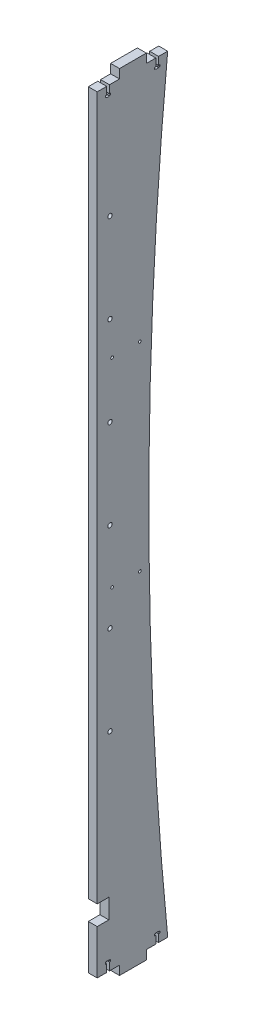
SolidWorks part; units mm, degrees
ref_plane "Płaszczyzna przednia" through (0, 0, 0) normal (0, 0, 1) x (1, 0, 0)
ref_plane "Płaszczyzna górna" through (0, 0, 0) normal (0, 1, 0) x (1, 0, 0)
ref_plane "Płaszczyzna prawa" through (0, 0, 0) normal (1, 0, 0) x (0, 0, -1)
ref_plane "Płaszczyzna2" through (248.5228, 0, 0) normal (-1, 0, 0) x (0, 0, 1)
sketch "Szkic11" plane through (248.5228, 0, 0) normal (-1, 0, 0) x (0, 0, 1)
  line L0 (-79.0014, 0) -> (0, 0)
  line L1 (0, 880) -> (-78.9552, 880)
  line L2 (-78.9552, 870) -> (-78.9552, 880)
  line L4 (-79.0014, 10) -> (-79.0014, 0)
  line L13 (0, 0) -> (0, 880)
  arc A2 (-79.0014, 10) -> (-78.9552, 870) centre (-4437.8003, 440.2341) ccw
extrude "Dodanie-wyciągnięcie1" add sketch "Szkic11" along normal blind 10
sketch "Szkic1" plane through (248.5228, 0, 0) normal (1, 0, 0) x (0, 0, -1)
  line L0 (85, 880) -> (85, 869.9)
  line L1 (85, 880) -> (55, 880)
  line L2 (85, 869.9) -> (55, 869.9)
  line L3 (55, 880) -> (55, 869.9)
  line L5 (25, 880) -> (25, 869.9)
  line L6 (25, 880) -> (0, 880)
  line L7 (25, 869.9) -> (0, 869.9)
  line L8 (0, 880) -> (0, 869.9)
  line L9 (0, 880) -> (78.9552, 880) construction
  dimension "D1" = 25
  dimension "D2" = 30
  dimension "D3" = 30
  dimension "D4" = 10.1
  dimension "D5" = 10.1
  dimension "D6" = 0
extrude "Wytnij-wyciągnięcie1" cut sketch "Szkic1" against normal blind 10
sketch "Szkic2" plane through (248.5228, 0, 0) normal (1, 0, 0) x (0, 0, -1)
  line L0 (10.6609, 869.9) -> (13.7609, 869.9)
  line L1 (10.6609, 869.9) -> (10.6609, 861.4)
  line L2 (13.7609, 869.9) -> (13.7609, 861.4)
  line L3 (10.6609, 858.9) -> (13.7609, 858.9)
  line L5 (9.2859, 859.4) -> (10.6609, 859.4)
  line L6 (9.2859, 859.4) -> (9.2859, 861.4)
  line L7 (15.1359, 859.4) -> (15.1359, 861.4)
  line L8 (9.2859, 861.4) -> (10.6609, 861.4)
  line L9 (13.7609, 859.4) -> (15.1359, 859.4)
  line L10 (10.6609, 859.4) -> (10.6609, 858.9)
  line L11 (13.7609, 859.4) -> (13.7609, 858.9)
  line L12 (13.7609, 861.4) -> (15.1359, 861.4)
  line L13 (0, 869.9) -> (25, 869.9) construction
  dimension "D1" = 11
  dimension "D2" = 5.85
  dimension "D3" = 3.1
  dimension "D4" = 1.375
  dimension "D5" = 2
  dimension "D6" = 0.5
  dimension "D7" = 0
extrude "Wytnij-wyciągnięcie2" cut sketch "Szkic2" against normal blind 10
pattern_linear "Szyk liniowy1" count 2 spacing 55 along (0, 0, -1) of "Wytnij-wyciągnięcie2"
ref_plane "Płaszczyzna1" through (0, 440, 0) normal (0, 1, 0) x (1, 0, 0)
sketch "Szkic7" plane through (248.5228, 0, 0) normal (1, 0, 0) x (0, 0, -1)
  circle A0 centre (14.3107, 742.237) radius 2.45 construction
  circle A1 centre (14.3107, 742.237) radius 2.45
extrude "Wytnij-wyciągnięcie5" cut sketch "Szkic7" against normal blind 10
pattern_linear "Szyk liniowy3" count 6 spacing 100 along (0, -1, 0) of "Wytnij-wyciągnięcie5"
sketch "Szkic8" plane through (248.5228, 0, 0) normal (1, 0, 0) x (0, 0, -1)
  line L0 (0, 82) -> (0, 60)
  line L6 (13, 82) -> (0, 82)
  line L11 (13, 60) -> (13, 82)
  line L12 (0, 60) -> (13, 60)
extrude "Wytnij-wyciągnięcie6" cut sketch "Szkic8" against normal blind 10
mirror "Lustro1" about plane through (0, 440, 0) normal (0, 1, 0) of "Szyk liniowy1", "Wytnij-wyciągnięcie2", "Wytnij-wyciągnięcie1"
sketch "Szkic12" plane through (238.5228, 0, 0) normal (-1, 0, 0) x (0, 0, 1)
  circle A0 centre (-47.7, 380.737) radius 1.55 construction
  circle A1 centre (-16.7, 380.737) radius 1.55 construction
  circle A2 centre (-47.7, 380.737) radius 1.55
  circle A3 centre (-16.7, 380.737) radius 1.55
extrude "Wytnij-wyciągnięcie7" cut sketch "Szkic12" against normal blind 10
pattern_linear "Szyk liniowy4" count 2 spacing 223 along (0, 1, 0) of "Wytnij-wyciągnięcie7"
equation "\"tolerancja_wpusy\"=0.2"
equation "\"dlugosc_wpustu_duzy\"=20"
equation "\"srednica_otworu_M3\"=3.1"
equation "\"szerokosc_nogi_T\"=3.1"
equation "\"dlugosc_T_30\"=11"
equation "\"grubosc_na_nakretke_kwadrat\"=2"
equation "\"szerokosc_na_nakretke_kwadrat\"=5.85"
equation "\"wyokosc_nadstawki_T\"=0.5"
equation "\"D1@Szkic2\"=\"dlugosc_T_30\""
equation "\"D2@Szkic2\"=\"szerokosc_na_nakretke_kwadrat\""
equation "\"D3@Szkic2\"=\"szerokosc_nogi_T\""
equation "\"D4@Szkic2\"=(\"szerokosc_na_nakretke_kwadrat\"-\"szerokosc_nogi_T\")/2"
equation "\"D5@Szkic2\"=\"grubosc_na_nakretke_kwadrat\""
equation "\"D6@Szkic2\"=\"wyokosc_nadstawki_T\""
